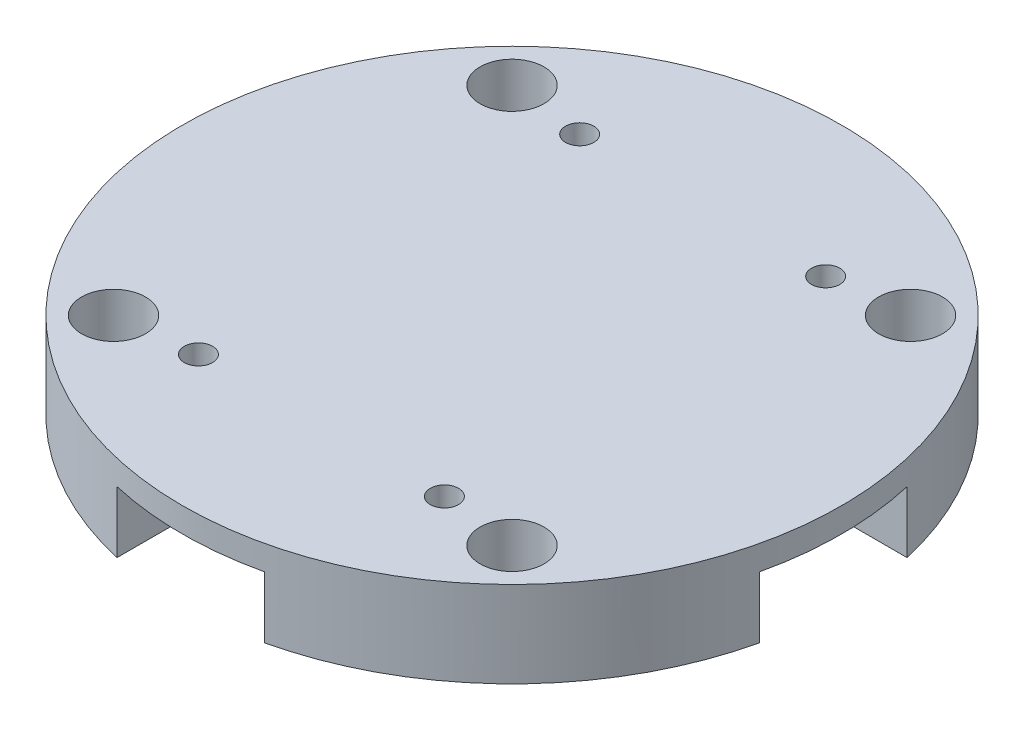
SolidWorks part; units mm, degrees
material "自定义塑料"
ref_plane "Front" through (0, 0, 0) normal (0, 0, 1) x (1, 0, 0)
ref_plane "Top" through (0, 0, 0) normal (0, 1, 0) x (1, 0, 0)
ref_plane "Right" through (0, 0, 0) normal (1, 0, 0) x (0, 0, -1)
sketch "草图4" plane through (0, 0, 0) normal (0, 1, 0) x (1, 0, 0)
  line L0 (1.3433, 6) -> (26.1197, 6)
  line L1 (-26.1197, 6) -> (-1.3433, 6)
  line L3 (-26.1197, -6) -> (-6, -6)
  line L5 (-26.1526, 5.8551) -> (-6, 1.3433) construction
  line L6 (-26.1526, -5.8551) -> (-6, -1.3433) construction
  line L8 (-6, 26.1197) -> (-6, 1.3433)
  line L9 (0, -26.8) -> (6, -26.8)
  line L10 (6, 26.1197) -> (6, 1.3433)
  line L11 (-5.8551, 26.1526) -> (-1.3433, 6) construction
  line L13 (1.3433, -6) -> (5.8551, -26.1526) construction
  line L14 (6, -1.3433) -> (26.1526, -5.8551) construction
  line L15 (6, 1.3433) -> (26.1526, 5.8551) construction
  line L16 (1.3433, 6) -> (5.8551, 26.1526) construction
  line L17 (1.3433, -6) -> (26.1197, -6)
  line L18 (-6, -1.3433) -> (-6, -26.1197)
  line L19 (6, -1.3433) -> (6, -26.1197)
  arc A0 (-26.1526, -5.8551) -> (-5.8551, -26.1526) centre (0, 0) ccw
  arc A1 (-5.8551, 26.1526) -> (-26.1526, 5.8551) centre (0, 0) ccw
  arc A2 (5.8551, -26.1526) -> (5.8551, 26.1526) centre (0, 0) ccw
  point P11 (-26.1197, 6)
  point P12 (26.1197, 6)
  point P13 (6, 26.1197)
  point P14 (-6, 26.1197)
  point P15 (-6, -26.1197)
  point P16 (6, -26.1197)
  point P17 (-26.1197, -6)
  point P18 (26.1197, -6)
  point P19 (6, -6)
  point P20 (-6, -6)
  point P21 (-6, 6)
  point P22 (6, 6)
  dimension "D1" = 53.6
extrude "凸台-拉伸2" add sketch "草图4" along normal blind 5 contours L8 A1 L1 | L0 A2 L10 | L3 A0 L18 | L19 A2 L17
sketch "草图5" plane through (0, 5, 0) normal (0, 1, 0) x (1, 0, 0)
  line L1 (16.2, 16.2) -> (-16.2, 16.2)
  line L2 (16.2, 16.2) -> (16.2, -16.2)
  line L3 (16.2, -16.2) -> (-16.2, -16.2)
  line L4 (-16.2, 16.2) -> (-16.2, -16.2)
  line L5 (16.2, 16.2) -> (-16.2, -16.2) construction
  line L6 (16.2, -16.2) -> (-16.2, 16.2) construction
  circle A0 centre (16.2, 16.2) radius 0.65
  circle A1 centre (16.2, -16.2) radius 0.65
  circle A2 centre (-16.2, -16.2) radius 0.65
  circle A3 centre (-16.2, 16.2) radius 0.65
  point P0 (0, 0)
  point P16 (0, 0)
  dimension "D1" = 4
extrude "切除-拉伸2" cut sketch "草图5" against normal blind 5 contours A0 | A1 | A2 | A3
sketch "草图7" plane through (0, 5, 0) normal (0, 1, 0) x (1, 0, 0)
  circle A0 centre (0, 0) radius 26.8
extrude "凸台-拉伸3" add sketch "草图7" along normal blind 2
sketch "草图6" plane through (0, 7, 0) normal (0, 1, 0) x (1, 0, 0)
  line L1 (16.2, 16.2) -> (-16.2, 16.2)
  line L2 (16.2, 16.2) -> (16.2, -16.2)
  line L3 (16.2, -16.2) -> (-16.2, -16.2)
  line L4 (-16.2, 16.2) -> (-16.2, -16.2)
  line L5 (16.2, 16.2) -> (-16.2, -16.2) construction
  line L6 (16.2, -16.2) -> (-16.2, 16.2) construction
  circle A0 centre (16.2, 16.2) radius 2.6
  circle A1 centre (16.2, -16.2) radius 2.6
  circle A2 centre (-16.2, -16.2) radius 2.6
  circle A3 centre (-16.2, 16.2) radius 2.6
  point P0 (0, 0)
  point P16 (0, 0)
  dimension "D1" = 4
extrude "切除-拉伸3" cut sketch "草图6" against normal blind 4.5 and the other way through all contours A0 | A1 | A3 | A2
sketch "草图8" plane through (0, 7, 0) normal (0, 1, 0) x (1, 0, 0)
  line L1 (22.7, -12.9) -> (-22.7, -12.9)
  line L2 (22.7, -12.9) -> (22.7, 12.9)
  line L3 (22.7, 12.9) -> (-22.7, 12.9)
  line L4 (-22.7, -12.9) -> (-22.7, 12.9)
  line L5 (22.7, -12.9) -> (-22.7, 12.9) construction
  line L6 (22.7, 12.9) -> (-22.7, -12.9) construction
  line L9 (13.6, -12.9) -> (-13.4159, -12.9)
  line L11 (13.6, 12.9) -> (-13.6, 12.9)
  line L15 (10, -15.5) -> (-10, -15.5)
  line L16 (10, -15.5) -> (10, 15.5)
  line L17 (10, 15.5) -> (-10, 15.5)
  line L18 (-10, -15.5) -> (-10, 15.5)
  line L19 (10, -15.5) -> (-10, 15.5) construction
  line L20 (10, 15.5) -> (-10, -15.5) construction
  circle A4 centre (10, -15.5) radius 1.15
  circle A5 centre (-10, -15.5) radius 1.15
  circle A6 centre (10, 15.5) radius 1.15
  circle A7 centre (-10, 15.5) radius 1.15
  point P0 (0, 0)
  point P5 (0, 0)
extrude "切除-拉伸4" cut sketch "草图8" against normal blind 3.3 contours A4 | A5 | A6 | A7
